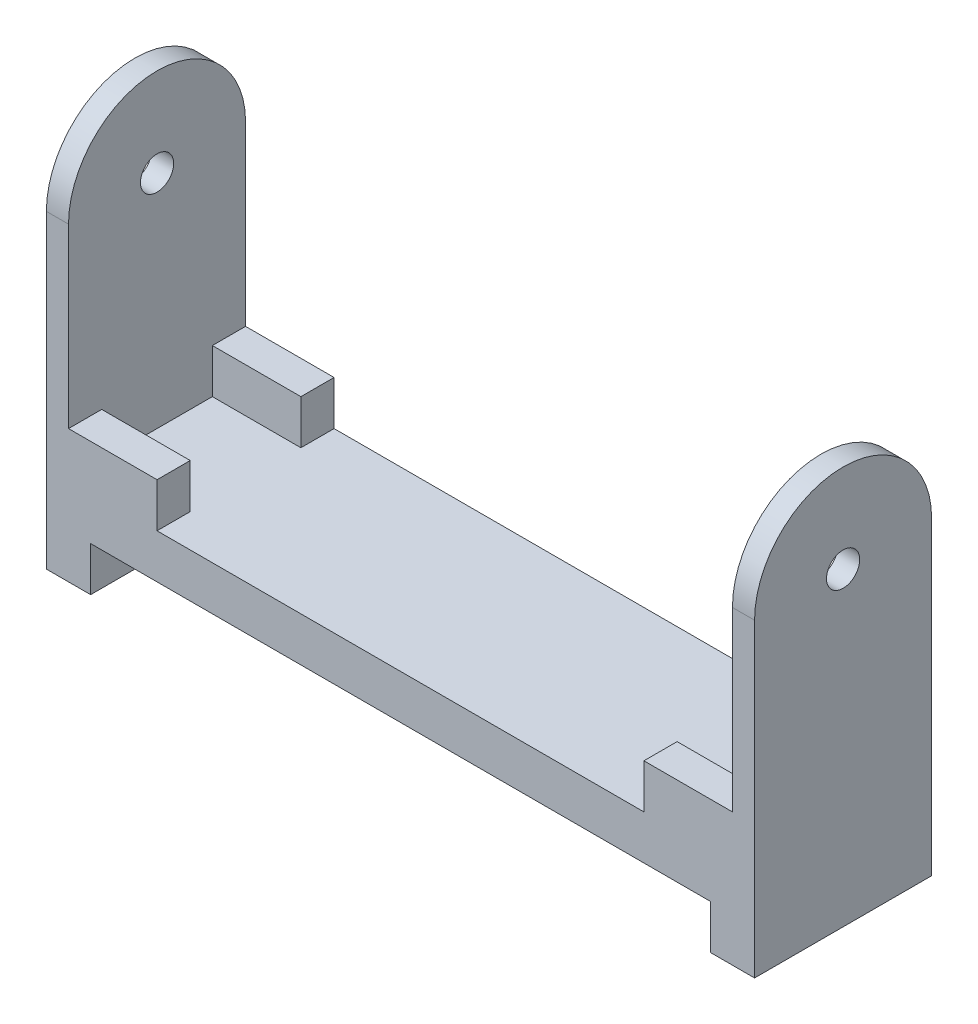
SolidWorks part; units mm, degrees
ref_plane "前基準面" through (0, 0, 0) normal (0, 0, 1) x (1, 0, 0)
ref_plane "上基準面" through (0, 0, 0) normal (0, 1, 0) x (1, 0, 0)
ref_plane "右基準面" through (0, 0, 0) normal (1, 0, 0) x (0, 0, -1)
sketch "草圖2" plane through (0, 0, 0) normal (1, 0, 0) x (0, 0, -1)
  line L0 (-40, 0) -> (-40, -120)
  line L1 (-40, -120) -> (40, -120)
  line L2 (40, -120) -> (40, 0)
  line L3 (0, 122.7537) -> (0, -552.4626) construction
  line L4 (-40, -100) -> (40, -100) construction
  circle A0 centre (0, 0) radius 7.5
  arc A1 (40, 0) -> (-40, 0) centre (0, 0) ccw
  dimension "D1" = 15
  dimension "D3" = 40
  dimension "D4" = 20
  dimension "D2" = 120
  dimension "D5" = 100
extrude "填料-伸長1" add sketch "草圖2" along normal blind 320
sketch "草圖3" plane through (0, 0, -40) normal (0, 0, -1) x (-1, 0, 0)
  line L0 (-310, 40) -> (-310, -100)
  line L1 (0, 40) -> (-320, 40) construction
  line L2 (-310, -100) -> (-10, -100)
  line L3 (-10, -100) -> (-10, 40)
  line L4 (-10, 40) -> (-310, 40)
  line L5 (-320, -120) -> (0, -120) construction
  line L6 (-320, -120) -> (-320, 0) construction
  line L7 (0, -120) -> (0, 0) construction
  dimension "D1" = 20
  dimension "D2" = 10
  dimension "D3" = 10
extrude "除料-伸長1" cut sketch "草圖3" against normal through all
sketch "草圖4" plane through (0, -120, 0) normal (0, -1, 0) x (1, 0, 0)
  line L0 (-11.0995, 0) -> (327.2431, 0) construction
  line L1 (160, 40) -> (160, -40) construction
  line L2 (320, 40) -> (0, 40) construction
  line L3 (320, -40) -> (0, -40) construction
  line L5 (0, 40) -> (20, 40)
  line L6 (0, 40) -> (0, -40)
  line L7 (0, -40) -> (20, -40)
  line L8 (20, 40) -> (20, -40)
  line L9 (320, -40) -> (300, -40)
  line L10 (320, -40) -> (320, 40)
  line L11 (320, 40) -> (300, 40)
  line L12 (300, -40) -> (300, 40)
  dimension "D1" = 20
  dimension "D2" = 20
extrude "填料-伸長2" add sketch "草圖4" along normal blind 20
sketch "草圖5" plane through (0, -140, 0) normal (0, -1, 0) x (1, 0, 0)
  line L0 (-15.8081, 0) -> (313.4538, 0) construction
  line L1 (10, 40) -> (10, -40) construction
  line L2 (20, 40) -> (0, 40) construction
  line L3 (0, -40) -> (20, -40) construction
  line L4 (310, -40) -> (310, 40) construction
  line L5 (300, -40) -> (320, -40) construction
  line L6 (320, 40) -> (300, 40) construction
  line L8 (15, -5) -> (5, -5)
  line L9 (15, -5) -> (15, 5)
  line L10 (15, 5) -> (5, 5)
  line L11 (5, -5) -> (5, 5)
  line L12 (10, 5) -> (10, -5) construction
  line L13 (15, 0) -> (5, 0) construction
  line L14 (315, -5) -> (305, -5)
  line L15 (315, -5) -> (315, 5)
  line L16 (315, 5) -> (305, 5)
  line L17 (305, -5) -> (305, 5)
  line L18 (310, 5) -> (310, -5) construction
  line L19 (315, 0) -> (305, 0) construction
  point P15 (10, 0)
  point P16 (10, 0)
  point P17 (310, 0)
  point P22 (310, 0)
  dimension "D1" = 10
  dimension "D2" = 10
  dimension "D3" = 10
  dimension "D4" = 10
extrude "螺絲預留孔" cut sketch "草圖5" against normal blind 30
sketch "草圖7" plane through (0, -100, 0) normal (0, 1, 0) x (1, 0, 0)
  line L0 (-20.5166, 0) -> (321.5256, 0) construction
  line L1 (10, 40) -> (50, 40)
  line L2 (10, 40) -> (10, 25)
  line L3 (10, 25) -> (50, 25)
  line L4 (50, 40) -> (50, 25)
  line L5 (10, -40) -> (50, -40)
  line L6 (10, -40) -> (10, -25)
  line L7 (10, -25) -> (50, -25)
  line L8 (50, -40) -> (50, -25)
  line L9 (310, -40) -> (270, -40)
  line L10 (310, -40) -> (310, -25)
  line L11 (310, -25) -> (270, -25)
  line L12 (270, -40) -> (270, -25)
  line L13 (310, 40) -> (270, 40)
  line L14 (310, 40) -> (310, 25)
  line L15 (310, 25) -> (270, 25)
  line L16 (270, 40) -> (270, 25)
  line L17 (310, 40) -> (310, -40) construction
  dimension "D1" = 40
  dimension "D2" = 15
  dimension "D3" = 40
extrude "放馬達" add sketch "草圖7" along normal blind 20
